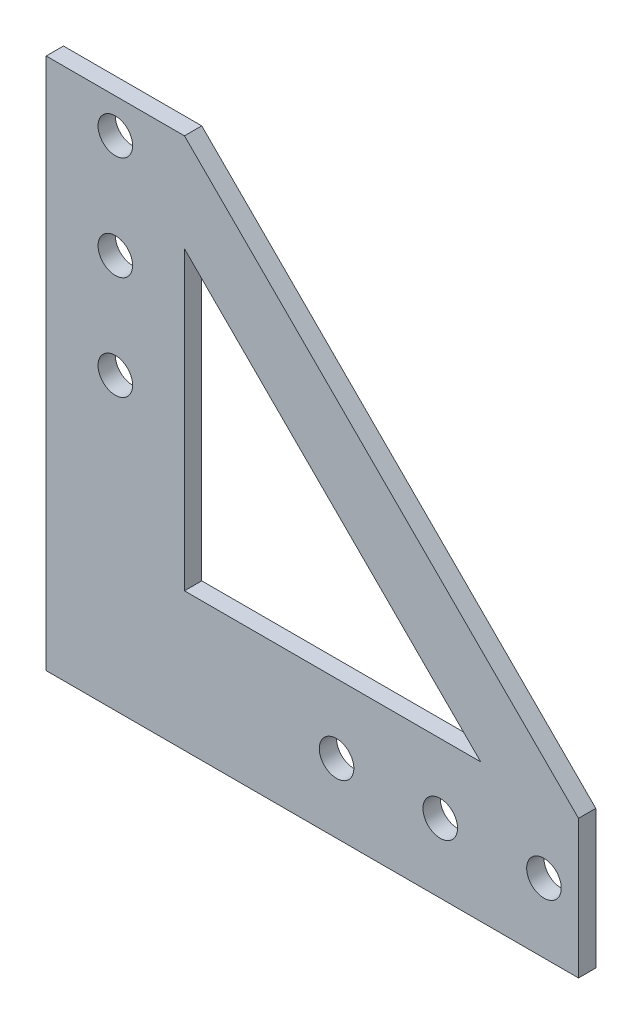
SolidWorks part; units mm, degrees
ref_plane "Front Plane" through (0, 0, 0) normal (0, 0, 1) x (1, 0, 0)
ref_plane "Top Plane" through (0, 0, 0) normal (0, 1, 0) x (1, 0, 0)
ref_plane "Right Plane" through (0, 0, 0) normal (1, 0, 0) x (0, 0, -1)
sketch "Sketch1" plane through (0, 0, 0) normal (0, 0, 1) x (1, 0, 0)
  line L0 (25.4, 97.79) -> (97.79, 25.4)
  line L1 (0, 0) -> (25.4, 0)
  line L2 (0, 0) -> (0, 97.79)
  line L3 (0, 97.79) -> (25.4, 97.79)
  line L4 (25.4, 25.4) -> (25.4, 79.8295)
  line L5 (0, 0) -> (97.79, 0)
  line L6 (0, 0) -> (0, 25.4)
  line L7 (25.4, 25.4) -> (79.8295, 25.4)
  line L8 (97.79, 0) -> (97.79, 25.4)
  line L9 (25.4, 79.8295) -> (79.8295, 25.4)
  line L10 (16.4197, 88.8097) -> (88.8097, 16.4197) construction
  dimension "D1" = 25.4
  dimension "D2" = 25.4
  dimension "D3" = 97.79
  dimension "D4" = 97.79
  dimension "D6" = 45
  dimension "D7" = 17.9605
  dimension "D5" = 12.7
extrude "Boss-Extrude1" add sketch "Sketch1" along normal blind 3.175 contours L5 L8 L7 L4 L3 L2 L1
sketch "Sketch2" plane through (0, 0, 3.175) normal (0, 0, 1) x (1, 0, 0)
  line L0 (0, 0) -> (97.79, 0) construction
  line L1 (0, 0) -> (0, 97.79) construction
  line L2 (25.4, 25.4) -> (79.8295, 25.4) construction
  circle A0 centre (53.34, 12.7) radius 3.175
  circle A1 centre (72.39, 12.7) radius 3.175
  circle A2 centre (12.7, 53.34) radius 3.175
  circle A3 centre (12.7, 72.39) radius 3.175
  circle A4 centre (12.7, 91.44) radius 3.175
  circle A5 centre (91.44, 12.7) radius 3.175
  dimension "D5" = 6.35
  dimension "D6" = 6.35
  dimension "D7" = 6.35
  dimension "D8" = 6.35
  dimension "D9" = 6.35
  dimension "D10" = 6.35
  dimension "D1" = 53.34
  dimension "D2" = 53.34
  dimension "D3" = 19.05
  dimension "D4" = 19.05
  dimension "D11" = 19.05
  dimension "D12" = 19.05
  dimension "D13" = 12.7
  dimension "D14" = 12.7
  dimension "D15" = 12.7
  dimension "D16" = 12.7
  dimension "D17" = 12.7
  dimension "D18" = 12.7
extrude "Cut-Extrude1" cut sketch "Sketch2" against normal through all
